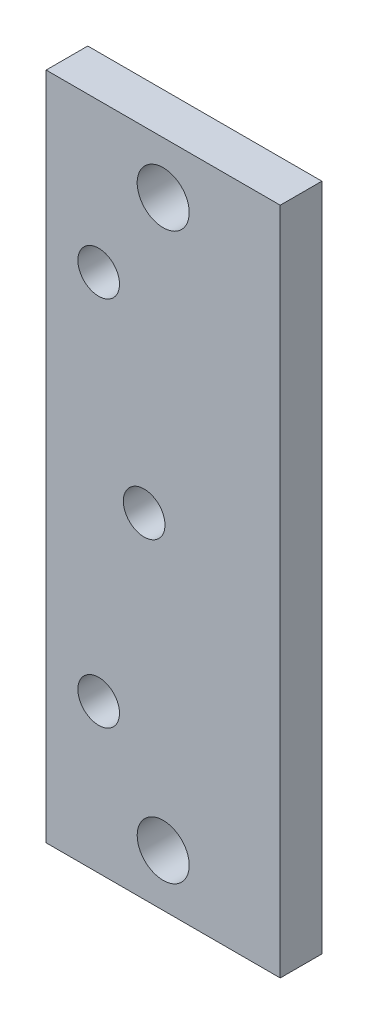
SolidWorks part; units mm, degrees
ref_plane "Front Plane" through (0, 0, 0) normal (0, 0, 1) x (1, 0, 0)
ref_plane "Top Plane" through (0, 0, 0) normal (0, 1, 0) x (1, 0, 0)
ref_plane "Right Plane" through (0, 0, 0) normal (1, 0, 0) x (0, 0, -1)
sketch "Sketch1" [suppressed] plane through (0, 0, 0) normal (0, 1, 0) x (1, 0, 0)
  line L1 (-38.1, -38.1) -> (38.1, -38.1) construction
  line L2 (-38.1, -38.1) -> (-38.1, 38.1) construction
  line L3 (-38.1, 38.1) -> (38.1, 38.1) construction
  line L4 (38.1, -38.1) -> (38.1, 38.1) construction
  line L5 (-38.1, -38.1) -> (38.1, 38.1) construction
  line L6 (-38.1, 38.1) -> (38.1, -38.1) construction
  line L7 (-20.575, -19.05) -> (20.575, -19.05) construction
  line L8 (-20.575, -19.05) -> (-20.575, 19.05) construction
  line L9 (-20.575, 19.05) -> (20.575, 19.05) construction
  line L10 (20.575, -19.05) -> (20.575, 19.05) construction
  line L11 (-20.575, -19.05) -> (20.575, 19.05) construction
  line L12 (-20.575, 19.05) -> (20.575, -19.05) construction
  line L13 (-3.175, -38.1) -> (3.175, -38.1) construction
  line L14 (-3.175, -38.1) -> (-3.175, 38.1) construction
  line L15 (-3.175, 38.1) -> (3.175, 38.1) construction
  line L16 (3.175, -38.1) -> (3.175, 38.1) construction
  line L17 (-3.175, -38.1) -> (3.175, 38.1) construction
  line L18 (-3.175, 38.1) -> (3.175, -38.1) construction
  line L19 (-4.7625, -38.1) -> (4.7625, -38.1) construction
  line L20 (-4.7625, -38.1) -> (-4.7625, 38.1) construction
  line L21 (-4.7625, 38.1) -> (4.7625, 38.1) construction
  line L22 (4.7625, -38.1) -> (4.7625, 38.1) construction
  line L23 (-4.7625, -38.1) -> (4.7625, 38.1) construction
  line L24 (-4.7625, 38.1) -> (4.7625, -38.1) construction
  line L25 (-5.715, 38.1) -> (5.715, 38.1) construction
  line L26 (-5.715, 38.1) -> (-5.715, -38.1) construction
  line L27 (-5.715, -38.1) -> (5.715, -38.1) construction
  line L28 (5.715, 38.1) -> (5.715, -38.1) construction
  line L29 (-5.715, 38.1) -> (5.715, -38.1) construction
  line L30 (-5.715, -38.1) -> (5.715, 38.1) construction
  circle A0 centre (-20.575, 19.05) radius 4.15 construction
  circle A1 centre (20.575, 19.05) radius 4.15 construction
  circle A2 centre (20.575, -19.05) radius 4.15 construction
  circle A3 centre (-20.575, -19.05) radius 4.15 construction
  point P0 (0, 0)
  point P5 (0, 0)
  point P11 (0, 0)
  point P16 (0, 0)
  point P25 (0, 0)
  point P30 (-24.725, 19.05)
  dimension "mounting hole" = 8.3
  dimension "Overall Height" = 76.2
  dimension "Overall Length" = 76.2
  dimension "hole to hole vert" = 38.1
  dimension "hole to hole horiz" = 41.15
  dimension "Pin Dia" = 6.35
  dimension "D1" = 9.525
  dimension "D2" = 11.43
sketch "Sketch2" [suppressed] plane through (0, 0, 0) normal (0, 0, 1) x (1, 0, 0)
  line L0 (-4.7625, 0) -> (-4.7625, 1.7125) construction
  line L1 (-3.175, 0) -> (-3.175, 1.7125) construction
  line L2 (-38.1, -3.05) -> (-38.1, 0) construction
  line L3 (-38.1, 0) -> (0, 0) construction
  line L4 (0, 0) -> (38.1, 0) construction
  line L5 (38.1, 0) -> (38.1, -3.05) construction
  line L6 (-38.1, -3.05) -> (0, -3.05) construction
  line L7 (-3.175, 0) -> (3.175, 0) construction
  circle A0 centre (0, 1.7125) radius 4.7625 construction
  circle A1 centre (0, 1.7125) radius 3.175 construction
  point P3 (-3.175, 0)
  point P4 (-4.7625, 0)
  point P12 (-38.1, 0)
  dimension "thickness" = 3.05
sketch "Sketch3" [suppressed] plane through (0, 0, 0) normal (0, 0, 1) x (1, 0, 0)
  line L2 (-38.1, 0) -> (38.1, 0) construction
  line L5 (-5.715, 0) -> (5.715, 0) construction
  line L6 (-38.1, 0) -> (38.1, 0) construction
  line L7 (-5.715, 0) -> (-5.715, -3.05)
  line L8 (-5.715, -3.05) -> (-38.1, -3.05)
  line L12 (-5.715, 0) -> (5.715, 0) construction
  line L13 (-38.1, -3.05) -> (-38.1, 0)
  line L14 (-38.1, 0) -> (-5.715, 0)
  line L15 (38.1, 0) -> (38.1, -3.05)
  line L16 (38.1, -3.05) -> (0, -3.05)
  line L20 (4.444, 0) -> (38.1, 0)
  arc A0 (4.444, 0) -> (0, -3.05) centre (0, 1.7125) ccw
  circle A10 centre (0, 1.7125) radius 3.175 construction
  circle A11 centre (0, 1.7125) radius 3.175 construction
  circle A12 centre (0, 1.7125) radius 3.375
  dimension "D1" = 0.2
extrude "Boss-Extrude1" [suppressed] add sketch "Sketch3" along normal up to vertex
sketch "Sketch5" [suppressed] plane through (0, 0, 0) normal (0, 0, 1) x (1, 0, 0)
  line L0 (38.1, 0) -> (38.1, -3.05)
  line L1 (38.1, -3.05) -> (5.715, -3.05)
  line L2 (-4.7625, 0) -> (4.7625, 0) construction
  line L3 (5.715, 0) -> (38.1, 0)
  line L5 (-38.1, -3.05) -> (0, -3.05) construction
  line L9 (0, -3.05) -> (-38.1, -3.05)
  line L10 (-38.1, -3.05) -> (-38.1, 0)
  line L11 (-38.1, 0) -> (-4.444, 0)
  line L12 (5.715, 0) -> (5.715, -3.05)
  line L13 (-38.1, 0) -> (38.1, 0) construction
  arc A3 (-4.444, 0) -> (0, -3.05) centre (0, 1.7125) cw
  circle A9 centre (0, 1.7125) radius 3.175 construction
  circle A10 centre (0, 1.7125) radius 3.175
  point P0 (-4.444, 0)
extrude "Boss-Extrude3" [suppressed] add sketch "Sketch5" against normal up to vertex separate body
sketch "Sketch4" [suppressed] plane through (0, 0, 0) normal (0, 0, 1) x (1, 0, 0)
  circle A0 centre (0, 1.7125) radius 3.175 construction
  circle A1 centre (0, 1.7125) radius 3.175
extrude "Boss-Extrude2" [suppressed] add sketch "Sketch4" along normal up to vertex and the other way up to vertex
combine bodies "Combine1" [suppressed] operation type add bodies to combine 124 117
combine bodies "Combine2" [suppressed] operation type add bodies to combine 116 119
sketch "Sketch6" [suppressed] plane through (0, 0, 0) normal (0, 1, 0) x (1, 0, 0)
  circle A0 centre (20.575, -19.05) radius 4.15 construction
  circle A1 centre (20.575, 19.05) radius 4.15 construction
  circle A2 centre (-20.575, -19.05) radius 4.15 construction
  circle A3 centre (-20.575, 19.05) radius 4.15 construction
  circle A4 centre (20.575, -19.05) radius 4.15
  circle A5 centre (20.575, 19.05) radius 4.15
  circle A6 centre (-20.575, -19.05) radius 4.15
  circle A7 centre (-20.575, 19.05) radius 4.15
extrude "Cut-Extrude1" [suppressed] cut sketch "Sketch6" against normal through all
fillet "Fillet2" [suppressed] radius 5
fillet "Fillet3" [suppressed] radius 5
sketch "Esquisse1" [suppressed] plane through (0, -3.05, 0) normal (0, -1, 0) x (1, 0, 0)
  line L0 (-20.575, 19.05) -> (-20.575, -19.05) construction
  line L1 (-38.1, 33.1) -> (-38.1, -33.1)
  line L2 (-5.715, 38.1) -> (-5.715, -38.1)
  line L3 (-33.1, -38.1) -> (0, -38.1) construction
  line L4 (-5.715, -38.1) -> (-33.1, -38.1)
  line L5 (-5.715, 38.1) -> (-33.1, 38.1)
  circle A0 centre (-20.575, 19.05) radius 4.15
  circle A1 centre (-20.575, -19.05) radius 4.15
  arc A2 (-33.1, -38.1) -> (-38.1, -33.1) centre (-33.1, -33.1) cw
  arc A3 (-33.1, 38.1) -> (-38.1, 33.1) centre (-33.1, 33.1) ccw
extrude "Boss.-Extru.1" [suppressed] add sketch "Esquisse1" along normal blind 6
sketch "Esquisse2" plane through (0, 0, 0) normal (0, 0, 1) x (-1, 0, 0)
  line L0 (-22.5, 0) -> (-22.5, 76.2) construction
  line L1 (-45, 128.646) -> (-45, 0)
  line L2 (0, 64.323) -> (0, 0)
  line L3 (0, 64.323) -> (-45, 64.323) construction
  line L4 (-5, 0) -> (-45, 0)
  line L5 (-5.55, 128.646) -> (-45, 128.646)
  line L7 (0, 128.646) -> (-5.55, 128.646)
  line L8 (0, 128.646) -> (0, 64.323)
  line L9 (0, 0) -> (-5, 0)
  circle A4 centre (-36.3894, 64.323) radius 3.175 construction
  circle A5 centre (-27.6518, 8.61) radius 3.175 construction
  circle A6 centre (-27.6518, 120.036) radius 3.175 construction
  circle A7 centre (-22.5, 10) radius 5
  circle A8 centre (-22.5, 118.646) radius 5
  dimension "D1" = 45
  dimension "D2" = 128.646
  dimension "D3" = 6.35
  dimension "D4" = 8.6106
  dimension "D5" = 8.61
  dimension "D6" = 6.35
  dimension "D7" = 17.3482
  dimension "D8" = 10
  dimension "D10" = 5.336
  dimension "D9" = 10
  dimension "D12" = 22.5
extrude "Boss.-Extru.2" add sketch "Esquisse2" along normal blind 8
sketch "Esquisse3" plane through (0, 0, 0) normal (0, 0, -1) x (-1, 0, 0)
  line L0 (-22.5, 0) -> (-22.5, -128.646) construction
  line L1 (0, -128.646) -> (-45, -128.646) construction
  line L2 (-5, -64.323) -> (-45, -64.323) construction
  line L3 (-17.5, -128.646) -> (-27.5, -128.646) construction
  line L4 (-17.5, -128.646) -> (-17.5, -108.646) construction
  line L5 (-17.5, -108.646) -> (-27.5, -108.646) construction
  line L6 (-27.5, -128.646) -> (-27.5, -108.646) construction
  line L7 (-45, -128.646) -> (-45, 0) construction
  line L8 (-27.5, -74.323) -> (-17.5, -74.323)
  line L9 (-27.5, -54.323) -> (-17.5, -54.323)
  line L14 (-27.5, -20) -> (-27.5, -54.323)
  line L15 (-27.5, -108.646) -> (-17.5, -108.646)
  line L16 (-17.5, -108.646) -> (-17.5, -74.323)
  line L17 (-17.5, -20) -> (-27.5, -20) construction
  line L22 (-27.5, 0) -> (-27.5, -20) construction
  line L23 (-17.5, 0) -> (-27.5, 0) construction
  line L24 (-17.5, 0) -> (-17.5, -20) construction
  line L25 (-17.5, -20) -> (-27.5, -20)
  line L26 (-17.5, -54.323) -> (-17.5, -20)
  line L27 (-17.5, -74.323) -> (-17.5, -64.323) construction
  line L28 (-17.5, -64.323) -> (-17.5, -54.323) construction
  line L29 (-27.5, -74.323) -> (-27.5, -108.646)
  line L30 (-27.5, -54.323) -> (-27.5, -64.323) construction
  line L31 (-27.5, -64.323) -> (-27.5, -74.323) construction
  circle A1 centre (-22.5, -10) radius 5 construction
  circle A2 centre (-22.5, -118.646) radius 5 construction
  dimension "D1" = 10
  dimension "D2" = 10
  dimension "D3" = 5
  dimension "D4" = 10
  dimension "D6" = 10
  dimension "D7" = 0
extrude "Boss.-Extru.3" add sketch "Esquisse3" along normal blind 6
sketch "Esquisse4" plane through (0, 0, 8) normal (0, 0, 1) x (1, 0, 0)
  line L0 (45, -128.646) -> (45, 0) construction
  line L1 (-18.5818, -20) -> (27.45, -20) construction
  line L2 (-18.5818, -20) -> (-18.5818, -108.646) construction
  line L3 (-18.5818, -108.646) -> (27.45, -108.646) construction
  line L4 (27.45, -20) -> (27.45, -108.646) construction
  line L5 (45, 0) -> (0, 0) construction
  line L6 (27.45, -64.323) -> (-18.5818, -64.323) construction
  circle A0 centre (10.1018, -28.6106) radius 4
  circle A1 centre (10.1018, -100.0354) radius 4
  circle A2 centre (18.84, -64.323) radius 4
  dimension "D4" = 8
  dimension "D5" = 8.6106
  dimension "D6" = 17.3482
  dimension "D7" = 8
  dimension "D8" = 8.61
  dimension "D1" = 88.646
  dimension "D2" = 17.55
  dimension "D3" = 20
extrude "Enlèv. mat.-Extru.1" cut sketch "Esquisse4" against normal up to next
equation "\"D1@Sketch1\"=\"Pin Dia@Sketch1\"*1.5"
equation "\"D2@Sketch1\"=\"D1@Sketch1\"*1.2"
